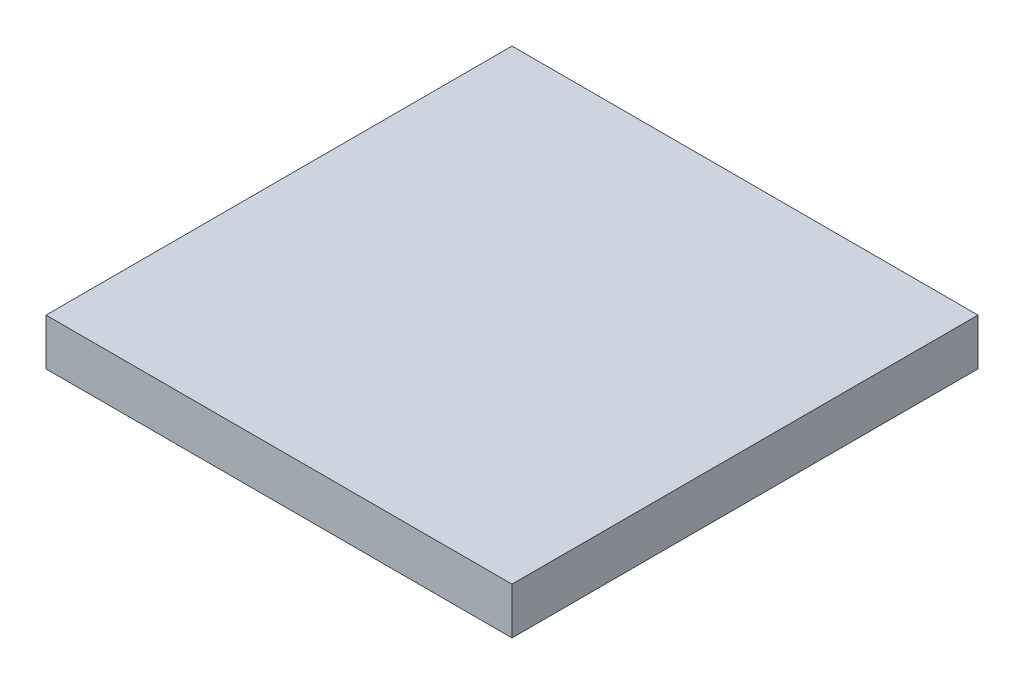
SolidWorks part; units mm, degrees
ref_plane "Front Plane" through (0, 0, 0) normal (0, 0, 1) x (1, 0, 0)
ref_plane "Top Plane" through (0, 0, 0) normal (0, 1, 0) x (1, 0, 0)
ref_plane "Right Plane" through (0, 0, 0) normal (1, 0, 0) x (0, 0, -1)
sketch "Sketch1" plane through (0, 0, 0) normal (0, 1, 0) x (1, 0, 0)
  line L1 (-63.5, 63.5) -> (63.5, 63.5)
  line L2 (-63.5, 63.5) -> (-63.5, -63.5)
  line L3 (-63.5, -63.5) -> (63.5, -63.5)
  line L4 (63.5, 63.5) -> (63.5, -63.5)
  line L5 (-63.5, 63.5) -> (63.5, -63.5) construction
  line L6 (-63.5, -63.5) -> (63.5, 63.5) construction
  point P0 (0, 0)
  dimension "D1" = 127
  dimension "D2" = 127
extrude "Boss-Extrude1" add sketch "Sketch1" along normal blind 12.7
